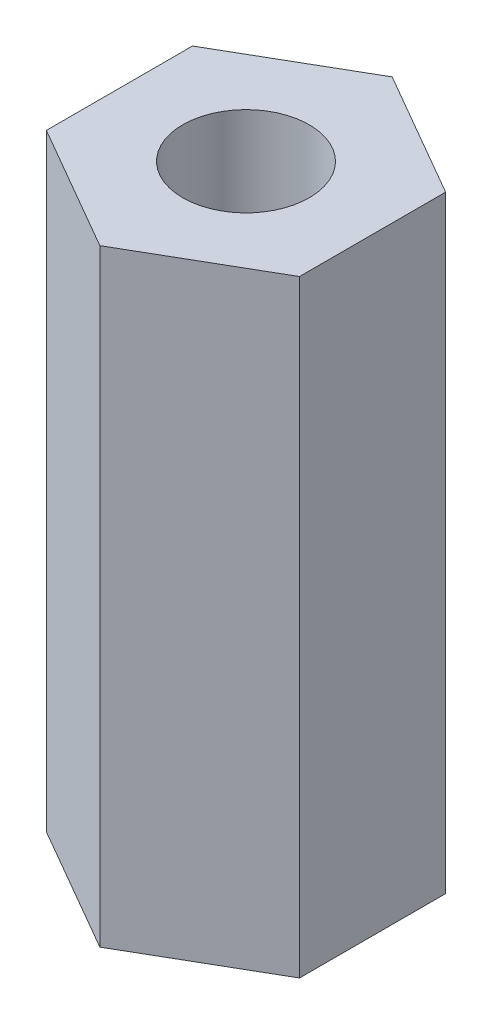
SolidWorks part; units mm, degrees
ref_plane "Front Plane" through (0, 0, 0) normal (0, 0, 1) x (1, 0, 0)
ref_plane "Top Plane" through (0, 0, 0) normal (0, 1, 0) x (1, 0, 0)
ref_plane "Right Plane" through (0, 0, 0) normal (1, 0, 0) x (0, 0, -1)
sketch "Sketch1" plane through (0, 0, 0) normal (0, 1, 0) x (1, 0, 0)
  line L1 (0, -7.3323) -> (6.35, -3.6662)
  line L2 (6.35, -3.6662) -> (6.35, 3.6662)
  line L3 (6.35, 3.6662) -> (0, 7.3323)
  line L4 (0, 7.3323) -> (-6.35, 3.6662)
  line L5 (-6.35, 3.6662) -> (-6.35, -3.6662)
  line L6 (-6.35, -3.6662) -> (0, -7.3323)
  circle A0 centre (0, 0) radius 6.35 construction
  dimension "D1" = 12.7
extrude "Boss-Extrude1" add sketch "Sketch1" along normal blind 30.48
sketch "Sketch2" plane through (0, 30.48, 0) normal (0, 1, 0) x (1, 0, 0)
  circle A0 centre (0, 0) radius 3.175
  dimension "D1" = 6.35
extrude "Cut-Extrude1" cut sketch "Sketch2" against normal through all both and the other way through all contours A0
